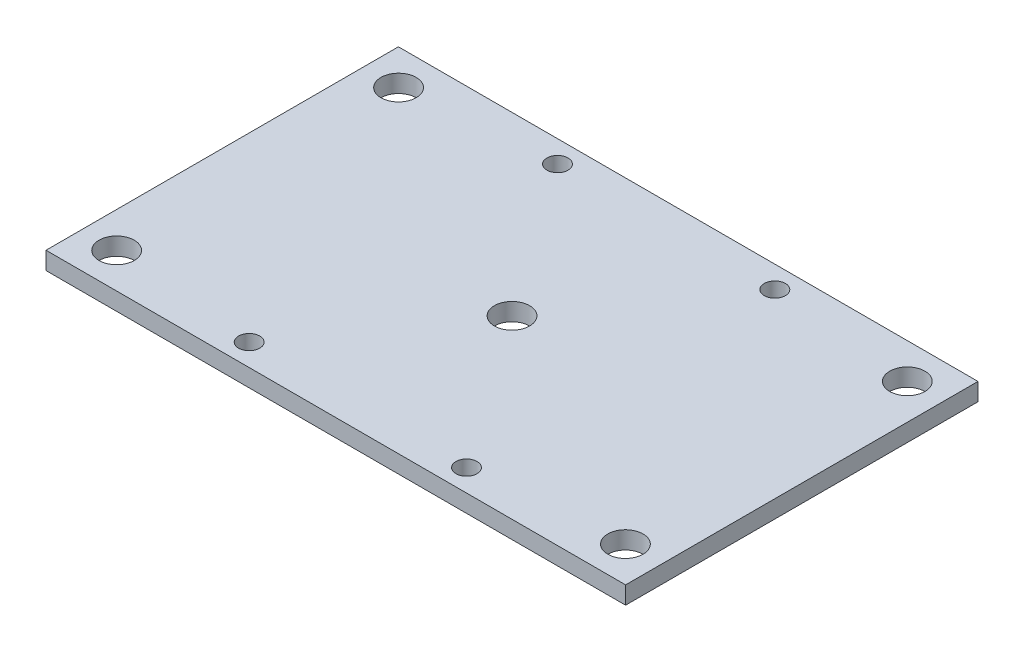
SolidWorks part; units mm, degrees
ref_plane "Plan de face" through (0, 0, 0) normal (0, 0, 1) x (1, 0, 0)
ref_plane "Plan de dessus" through (0, 0, 0) normal (0, 1, 0) x (1, 0, 0)
ref_plane "Plan de droite" through (0, 0, 0) normal (1, 0, 0) x (0, 0, -1)
sketch "Esquisse1" plane through (0, 0, 0) normal (0, 1, 0) x (1, 0, 0)
  line L0 (-72.19, 40) -> (-72.19, -40) construction
  line L1 (-90.2375, -50) -> (90.2375, -50)
  line L2 (-90.2375, -50) -> (-90.2375, 50)
  line L3 (-90.2375, 50) -> (90.2375, 50)
  line L4 (90.2375, -50) -> (90.2375, 50)
  line L5 (-90.2375, -50) -> (90.2375, 50) construction
  line L6 (-90.2375, 50) -> (90.2375, -50) construction
  line L7 (-72.19, 40) -> (72.19, 40) construction
  line L8 (0, 0) -> (-104.2, 0) construction
  line L9 (0, 0) -> (0, 50) construction
  circle A0 centre (-72.19, 40) radius 5
  circle A1 centre (72.19, 40) radius 5
  circle A2 centre (72.19, -40) radius 5
  circle A3 centre (-72.19, -40) radius 5
  circle A4 centre (0, 0) radius 5
  point P0 (0, 0)
  dimension "D4" = 10
  dimension "D5" = 10
  dimension "D1" = 100
  dimension "D2" = 80
  dimension "D3" = 144.38
extrude "Boss.-Extru.1" add sketch "Esquisse1" along normal blind 5
sketch "Esquisse2" plane through (0, 5, 0) normal (0, 1, 0) x (1, 0, 0)
  line L0 (-90.2375, -50) -> (90.2375, -50) construction
  line L1 (-90.2375, 50) -> (-82.2375, 50)
  line L2 (-90.2375, 50) -> (-90.2375, -50)
  line L3 (-90.2375, -50) -> (-82.2375, -50)
  line L4 (-82.2375, 50) -> (-82.2375, -50)
  line L5 (0, 0) -> (0, 50) construction
  line L6 (90.2375, 50) -> (-90.2375, 50) construction
  line L7 (82.2375, 50) -> (82.2375, -50)
  line L8 (90.2375, -50) -> (82.2375, -50)
  line L9 (90.2375, 50) -> (90.2375, -50)
  line L10 (90.2375, 50) -> (82.2375, 50)
  dimension "D1" = 8
extrude "Enlèv. mat.-Extru.1" cut sketch "Esquisse2" against normal up to surface (5 mm away) up to face at (-72.19, 0, 35)
sketch "Esquisse3" plane through (0, 5, 0) normal (0, 1, 0) x (1, 0, 0)
  line L0 (0, 0) -> (0, 50) construction
  line L1 (82.2375, 50) -> (-82.2375, 50) construction
  line L2 (0, 50) -> (-82.2375, 0) construction
  line L3 (-82.2375, -50) -> (-82.2375, 50) construction
  line L4 (-82.2375, 0) -> (0, -50) construction
  line L5 (-82.2375, -50) -> (82.2375, -50) construction
  line L6 (0, -50) -> (82.2375, 0) construction
  line L7 (82.2375, 50) -> (82.2375, -50) construction
  line L8 (82.2375, 0) -> (0, 50) construction
  line L9 (-41.1187, 25) -> (-41.1187, 50) construction
  line L10 (-41.1187, 50) -> (0, 25) construction
  line L11 (0, 25) -> (-20.5594, 25) construction
  line L12 (-20.5594, 25) -> (-20.5594, 50) construction
  line L13 (-20.5594, 50) -> (0, 37.5) construction
  line L14 (0, 37.5) -> (-10.2797, 37.5) construction
  line L15 (-10.2797, 37.5) -> (-10.2797, 50) construction
  line L16 (-10.2797, 43.75) -> (-41.1187, 43.75) construction
  line L17 (0, 0) -> (17.228, 0) construction
  circle A0 centre (-30.8391, 43.75) radius 3
  circle A1 centre (30.8391, 43.75) radius 3
  circle A2 centre (30.8391, -43.75) radius 3
  circle A3 centre (-30.8391, -43.75) radius 3
  dimension "D1" = 6
extrude "Enlèv. mat.-Extru.2" cut sketch "Esquisse3" against normal up to surface (5 mm away) up to face at (0, 0, 0)
